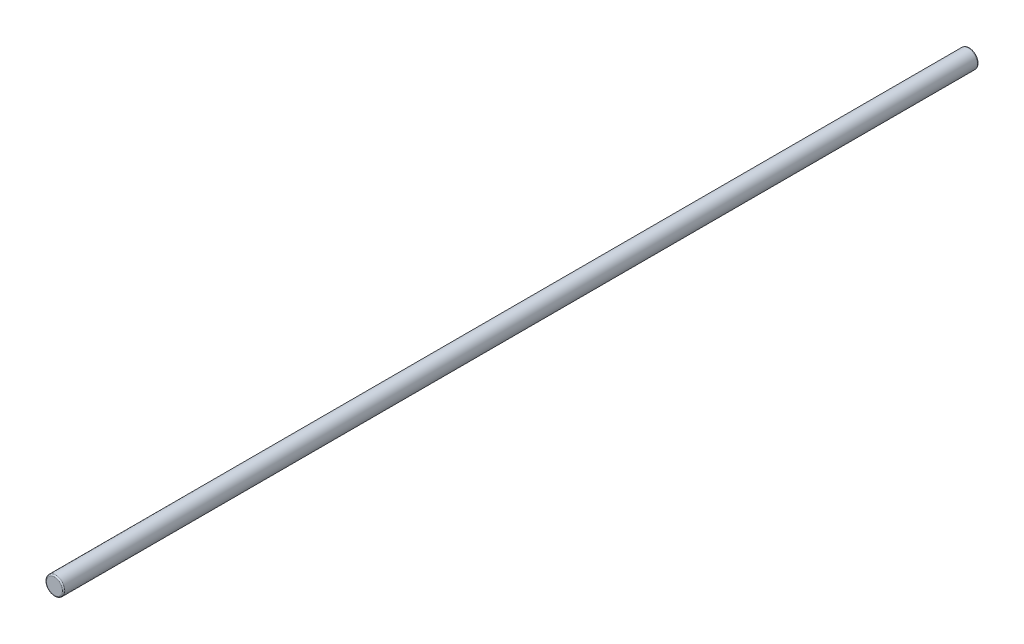
SolidWorks part; units mm, degrees
material "1.4000 (X6Cr13)"
ref_plane "Alzado" through (0, 0, 0) normal (0, 0, 1) x (1, 0, 0)
ref_plane "Planta" through (0, 0, 0) normal (0, 1, 0) x (1, 0, 0)
ref_plane "Vista lateral" through (0, 0, 0) normal (1, 0, 0) x (0, 0, -1)
sketch "Croquis1" plane through (0, 0, 0) normal (0, 0, 1) x (1, 0, 0)
  circle A0 centre (0, 0) radius 1.5
  dimension "D1" = 3
extrude "Saliente-Extruir1" add sketch "Croquis1" along normal blind 150
fillet "Redondeo2" radius 0.2 1 edges at (1.5, 0, 150)
fillet "Redondeo3" radius 0.2 1 edges at (1.5, 0, 0)
